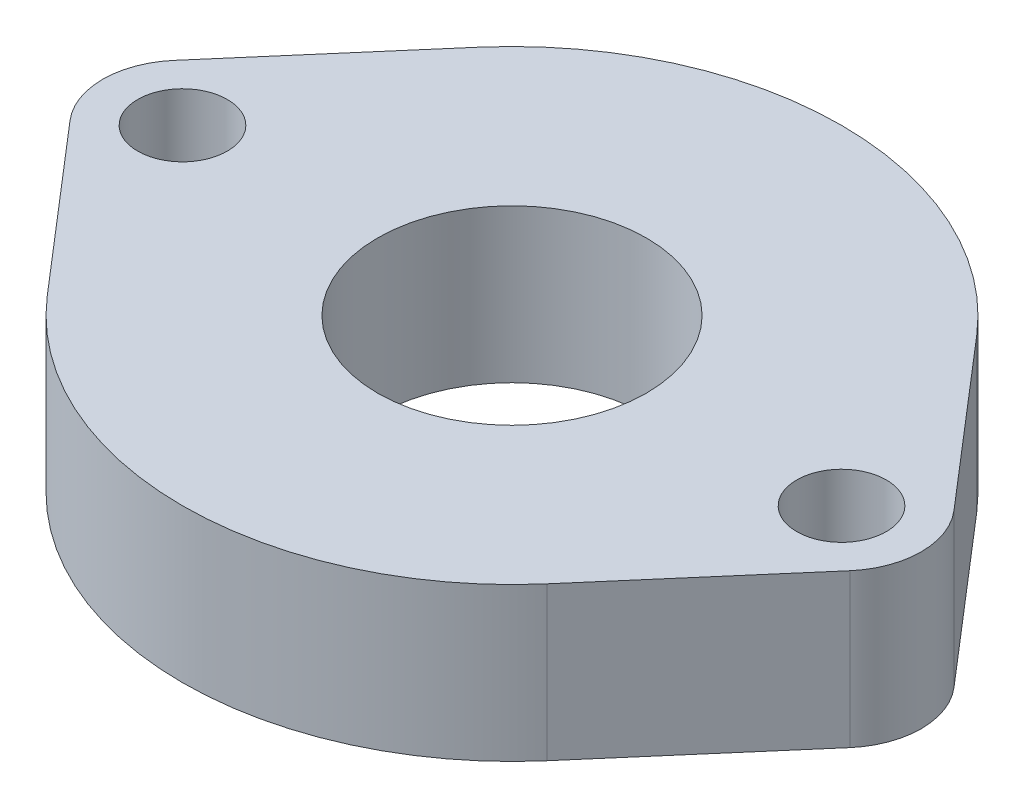
SolidWorks part; units mm, degrees
ref_plane "Front Plane" through (0, 0, 0) normal (0, 0, 1) x (1, 0, 0)
ref_plane "Top Plane" through (0, 0, 0) normal (0, 1, 0) x (1, 0, 0)
ref_plane "Right Plane" through (0, 0, 0) normal (1, 0, 0) x (0, 0, -1)
sketch "Sketch1" plane through (0, 0, 0) normal (0, 1, 0) x (1, 0, 0)
  line L0 (-15.0296, 2.0046) -> (-9.6266, 8.2836)
  line L1 (9.6266, 8.2836) -> (15.0296, 2.0046)
  line L2 (-15.0296, -2.0046) -> (-9.6266, -8.2836)
  line L3 (15.0296, -2.0046) -> (9.6266, -8.2836)
  line L5 (-55, 0) -> (55, 0) construction
  circle A0 centre (0, 0) radius 8.1661 construction
  arc A1 (-9.6266, -8.2836) -> (9.6266, -8.2836) centre (0, 0) ccw
  circle A2 centre (-12.7, 0) radius 1.7272
  circle A3 centre (12.7, 0) radius 1.7272
  arc A4 (-15.0296, 2.0046) -> (-15.0296, -2.0046) centre (-12.7, 0) ccw
  arc A5 (15.0296, -2.0046) -> (15.0296, 2.0046) centre (12.7, 0) ccw
  arc A6 (9.6266, 8.2836) -> (-9.6266, 8.2836) centre (0, 0) ccw
  dimension "D1" = 16.3322
  dimension "D2" = 25.4
  dimension "D3" = 6.1468
  dimension "D4" = 3.4544
extrude "Boss-Extrude1" add sketch "Sketch1" along normal blind 5.9055
sketch "Sketch2" plane through (0, 0, 0) normal (0, -1, 0) x (1, 0, 0)
  circle A0 centre (0, 0) radius 10.3187
  dimension "D1" = 20.6375
extrude "Boss-Extrude2" [suppressed] add sketch "Sketch2" along normal blind 28.575
sketch "Sketch3" plane through (0, 5.9055, 0) normal (0, 1, 0) x (1, 0, 0)
  circle A0 centre (0, 0) radius 8.1534
  dimension "D1" = 16.3068
extrude "Cut-Extrude1" [suppressed] cut sketch "Sketch3" against normal blind 7.62
sketch "Sketch4" plane through (0, 5.9055, 0) normal (0, 1, 0) x (1, 0, 0)
  circle A0 centre (0, 0) radius 6.7945
  dimension "D1" = 13.589
extrude "Cut-Extrude2" [suppressed] cut sketch "Sketch4" against normal blind 16.256
sketch "Sketch5" [suppressed] plane through (0, 5.9055, 0) normal (0, 1, 0) x (1, 0, 0)
  circle A0 centre (0, 0) radius 5.08
  dimension "D1" = 10.16
extrude "Cut-Extrude3" [suppressed] cut sketch "Sketch5" against normal through all
sketch "Sketch6" plane through (0, 5.9055, 0) normal (0, 1, 0) x (1, 0, 0)
  circle A0 centre (0, 0) radius 5.1816
  dimension "D1" = 10.3632
extrude "Cut-Extrude4" cut sketch "Sketch6" against normal through all
